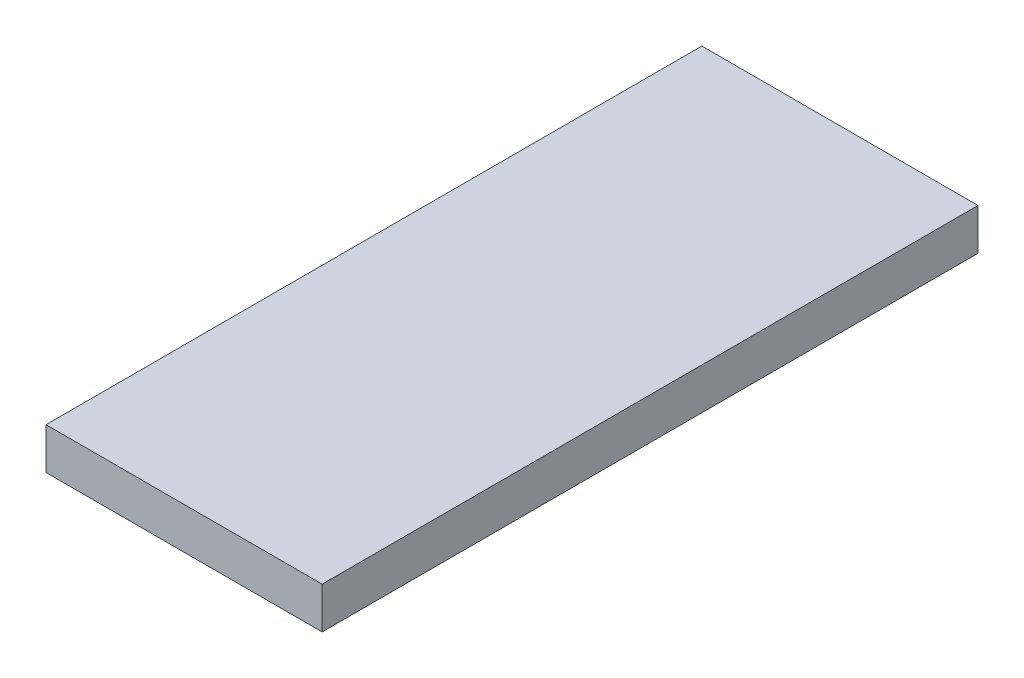
SolidWorks part; units mm, degrees
ref_plane "Front Plane" through (0, 0, 0) normal (0, 0, 1) x (1, 0, 0)
ref_plane "Top Plane" through (0, 0, 0) normal (0, 1, 0) x (1, 0, 0)
ref_plane "Right Plane" through (0, 0, 0) normal (1, 0, 0) x (0, 0, -1)
sketch "Sketch1" plane through (0, 0, 0) normal (0, 1, 0) x (1, 0, 0)
  line L1 (0, 0) -> (16, 0)
  line L2 (0, 0) -> (0, 38)
  line L3 (0, 38) -> (16, 38)
  line L4 (16, 0) -> (16, 38)
  dimension "D1" = 38
  dimension "D2" = 16
extrude "Boss-Extrude1" add sketch "Sketch1" along normal blind 2.4
